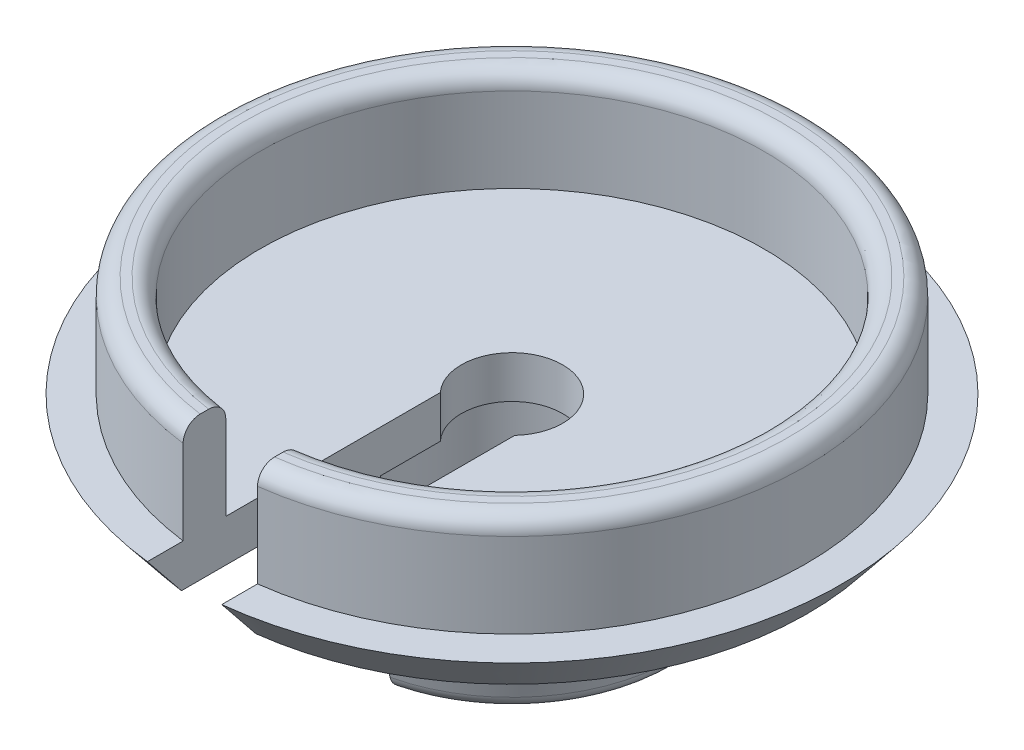
SolidWorks part; units mm, degrees
ref_plane "Front Plane" through (0, 0, 0) normal (0, 0, 1) x (1, 0, 0)
ref_plane "Top Plane" through (0, 0, 0) normal (0, 1, 0) x (1, 0, 0)
ref_plane "Right Plane" through (0, 0, 0) normal (1, 0, 0) x (0, 0, -1)
sketch "Sketch1" plane through (0, 0, 0) normal (0, 0, 1) x (1, 0, 0)
  line L0 (0, -16.6019) -> (0, 13.4857) construction
  line L1 (1.5, 0) -> (1.5, 1.25)
  line L2 (1.5, 1.25) -> (7.45, 1.25)
  line L3 (7.45, 1.25) -> (7.45, 4.25)
  line L4 (7.45, 4.25) -> (8.7, 4.25)
  line L5 (8.7, 4.25) -> (8.7, 1.25)
  line L6 (8.7, 1.25) -> (9.75, 1.25)
  line L7 (9.75, 1.25) -> (8.75, 0)
  line L8 (8.75, 0) -> (5.5, 0)
  line L9 (5.5, 0) -> (4.75, -3.5)
  line L10 (4.75, -3.5) -> (3, -3.5)
  line L11 (3, -3.5) -> (3, 0)
  line L12 (3, 0) -> (1.5, 0)
  dimension "D1" = 1.5
  dimension "D2" = 8.7
  dimension "D3" = 9.75
  dimension "D4" = 7.45
  dimension "D5" = 5.5
  dimension "D6" = 4.75
  dimension "D7" = 3
  dimension "D8" = 7.75
  dimension "D9" = 3
  dimension "D10" = 3
  dimension "D11" = 3.5
  dimension "D12" = 3.5
  dimension "D13" = 3.25
revolve "Revolve1" add sketch "Sketch1" angle 360 about L0
fillet "Fillet1" radius 0.5 4 edges at (0, 4.25, -7.45) (0, 4.25, -8.7) (0, -3.5, -4.75) (0, 0, -5.5)
sketch "Sketch2" plane through (0, 0, 0) normal (0, 1, 0) x (1, 0, 0)
  line L0 (0, 0) -> (0, -12.021) construction
  line L1 (-1.1, 0) -> (-1.1, -12.021)
  line L2 (1.1, 0) -> (1.1, -12.021)
  line L3 (-1.1, 0) -> (1.1, 0)
  line L4 (-1.1, -12.021) -> (1.1, -12.021)
  dimension "D1" = 1.1
  dimension "D2" = 1.1
extrude "Cut-Extrude1" cut sketch "Sketch2" against normal mid plane 10
